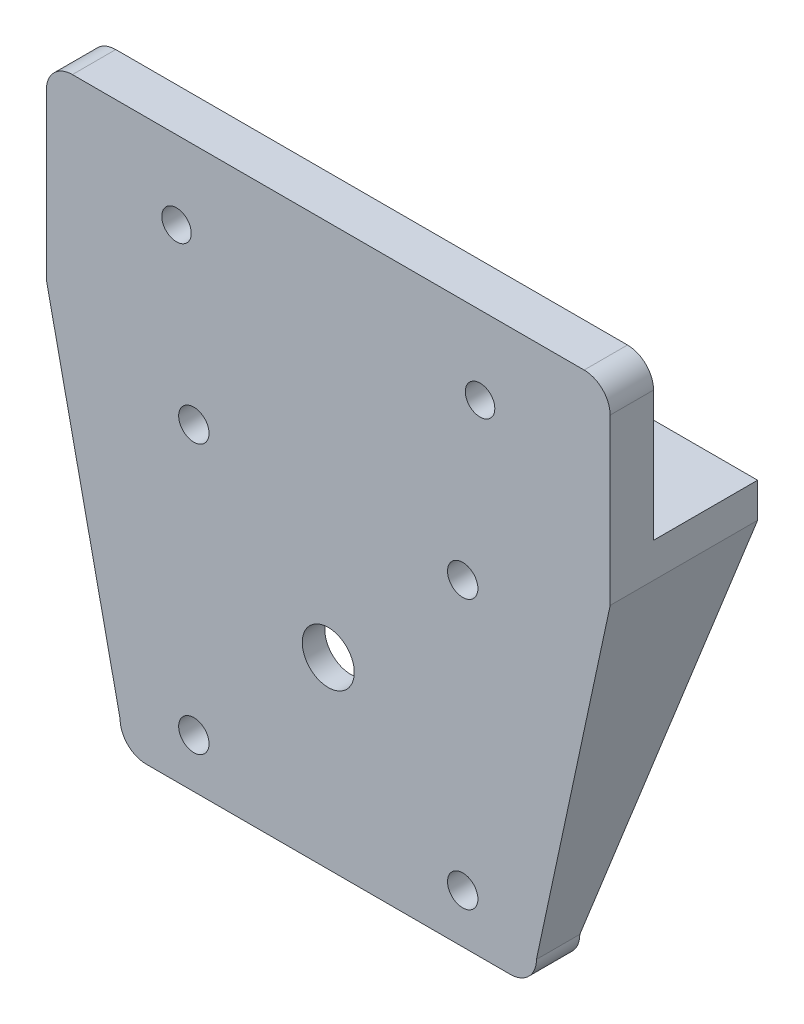
SolidWorks part; units mm, degrees
ref_plane "Ebene vorne" through (0, 0, 0) normal (0, 0, 1) x (1, 0, 0)
ref_plane "Ebene oben" through (0, 0, 0) normal (0, 1, 0) x (1, 0, 0)
ref_plane "Ebene rechts" through (0, 0, 0) normal (1, 0, 0) x (0, 0, -1)
sketch "Skizze1" plane through (0, 0, 0) normal (0, 0, 1) x (1, 0, 0)
  line L1 (-21, 32.3) -> (21, 32.3)
  line L2 (-24, 29.3) -> (-24, -29.3)
  line L3 (-21, -32.3) -> (21, -32.3)
  line L4 (24, 29.3) -> (24, -29.3)
  line L5 (-24, 32.3) -> (24, -32.3) construction
  line L6 (-24, -32.3) -> (24, 32.3) construction
  arc A0 (21, 32.3) -> (24, 29.3) centre (21, 29.3) cw
  arc A1 (-24, -29.3) -> (-21, -32.3) centre (-21, -29.3) ccw
  arc A2 (-21, 32.3) -> (-24, 29.3) centre (-21, 29.3) ccw
  arc A3 (21, -32.3) -> (24, -29.3) centre (21, -29.3) ccw
  point P0 (0, 0)
  dimension "D1" = 3
  dimension "D2" = 48
  dimension "D3" = 64.6
extrude "Aufsatz-Linear austragen1" add sketch "Skizze1" along normal blind 5
sketch "Skizze2" plane through (0, 0, 5) normal (0, 0, 1) x (1, 0, 0)
  line L0 (-15.5, 4.35) -> (15.5, -26.65) construction
  line L1 (-21, -32.3) -> (21, -32.3) construction
  line L2 (15.5, 4.35) -> (-15.5, -26.65) construction
  line L5 (21, 32.3) -> (-21, 32.3) construction
  line L6 (-17.5, 23.3) -> (17.5, 23.3) construction
  circle A0 centre (-15.5, -26.65) radius 1.75
  circle A1 centre (15.5, -26.65) radius 1.75
  circle A2 centre (15.5, 4.35) radius 1.75
  circle A3 centre (-15.5, 4.35) radius 1.75
  circle A4 centre (-17.5, 23.3) radius 1.7
  circle A5 centre (17.5, 23.3) radius 1.7
  point P12 (0, 32.3)
  point P13 (0, -11.15)
  point P15 (0, 23.3)
  point P23 (0, -32.3)
  dimension "D1" = 3.5
  dimension "D6" = 3.4
  dimension "D2" = 31
  dimension "D3" = 31
  dimension "D5" = 5.65
  dimension "D7" = 9
  dimension "D8" = 35
extrude "Schnitt-Linear austragen1" cut sketch "Skizze2" against normal through all
sketch "Skizze3" plane through (0, 0, 0) normal (0, 0, -1) x (-1, 0, 0)
  line L0 (15.5, -26.65) -> (-15.5, 4.35) construction
  line L1 (15.5, 4.35) -> (-15.5, -26.65) construction
  circle A0 centre (0, -11.15) radius 11.15
  dimension "D1" = 22.3
extrude "Schnitt-Linear austragen2" cut sketch "Skizze3" against normal blind 2.4
sketch "Skizze4" plane through (0, 0, 2.4) normal (0, 0, -1) x (-1, 0, 0)
  circle A0 centre (0, -11.15) radius 3
  dimension "D1" = 6
extrude "Schnitt-Linear austragen3" cut sketch "Skizze4" against normal through all
sketch "Skizze5" plane through (0, 0, 5) normal (0, 0, 1) x (1, 0, 0)
  line L0 (-24, 29.3) -> (-24, -29.3) construction
  line L1 (-17, 30.3) -> (-15.0597, 30.7851)
  line L2 (-17, 30.3) -> (-10, 2.3)
  line L3 (-10, 2.3) -> (-8.0597, 2.7851)
  line L4 (-15.0597, 30.7851) -> (-8.0597, 2.7851)
  line L5 (-17, 30.3) -> (-8.0597, 2.7851) construction
  line L6 (-10, 2.3) -> (-15.0597, 30.7851) construction
  line L7 (21, 32.3) -> (-21, 32.3) construction
  line L9 (-10, 30.3) -> (-8, 30.3)
  line L10 (-10, 30.3) -> (-10, 2.3)
  line L11 (-10, 2.3) -> (-8, 2.3)
  line L12 (-8, 30.3) -> (-8, 2.3)
  line L13 (-10, 30.3) -> (-8, 2.3) construction
  line L14 (-10, 2.3) -> (-8, 30.3) construction
  line L15 (-10, -12.7) -> (-8, -12.7)
  line L16 (-10, -12.7) -> (-10, 2.3)
  line L17 (-10, 2.3) -> (-8, 2.3)
  line L18 (-8, -12.7) -> (-8, 2.3)
  line L19 (-10, -12.7) -> (-8, 2.3) construction
  line L20 (-10, 2.3) -> (-8, -12.7) construction
  point P0 (-12.5299, 16.5425)
  point P9 (-9, 16.3)
  point P14 (-9, -5.2)
  dimension "D1" = 2
  dimension "D2" = 7
  dimension "D3" = 2
  dimension "D4" = 2
  dimension "D5" = 16
  dimension "D6" = 30
  dimension "D7" = 2
  dimension "D8" = 15
extrude "Aufsatz-Linear austragen2" [suppressed] add sketch "Skizze5" along normal blind 4 contours L10 L4 L1 L2 | L4 L10 L3 | L12 L9 L10 L4 L3 L11 | L16 L15 L18 L17
ref_plane "Ebene1" through (0, 0, 0) normal (-1, 0, 0) x (0, 0, 1)
mirror "Spiegeln1" [suppressed] about plane through (0, 0, 0) normal (-1, 0, 0)
sketch "Skizze6" [suppressed] plane through (0, 0, 3.2) normal (0, 0, 1) x (1, 0, 0)
  line L0 (0, 3.96) -> (0, -3.96) construction
  line L1 (-1, 30.3) -> (1, 30.3)
  line L2 (-1, 30.3) -> (-1, 2.6)
  line L3 (-1, 2.6) -> (1, 2.6)
  line L4 (1, 30.3) -> (1, 2.6)
  line L5 (-1, 30.3) -> (1, 2.6) construction
  line L6 (-1, 2.6) -> (1, 30.3) construction
  line L7 (-9.15, 30.3) -> (-7.15, 30.3) construction
  circle A0 centre (-15.5, 4.35) radius 1.75 construction
  point P0 (0, 16.45)
  dimension "D1" = 2
extrude "Aufsatz-Linear austragen3" [suppressed] add sketch "Skizze6" along normal blind 4
sketch "Skizze8" [suppressed] plane through (0, 0, 3.2) normal (0, 0, 1) x (1, 0, 0)
  line L5 (20.15, 32.3) -> (-20.15, 32.3) construction
  line L6 (-19.95, -29.3) -> (-23.15, -29.3)
  line L7 (-19.95, -29.3) -> (-19.95, 32.3)
  line L8 (-19.95, 32.3) -> (-20.15, 32.3)
  line L9 (-23.15, -29.3) -> (-23.15, 29.3)
  line L10 (-19.95, -29.3) -> (-23.15, 32.3) construction
  line L11 (-19.95, 32.3) -> (-23.15, -29.3) construction
  arc A0 (-20.15, 32.3) -> (-23.15, 29.3) centre (-20.15, 29.3) ccw
  point P0 (-21.55, 1.5)
  dimension "D2" = 3
  dimension "D1" = 3.2
extrude "Aufsatz-Linear austragen5" [suppressed] add sketch "Skizze8" along normal blind 4
mirror "Spiegeln2" [suppressed] about plane through (0, 0, 0) normal (-1, 0, 0)
sketch "Skizze9" plane through (0, 0, 0) normal (0, 0, -1) x (-1, 0, 0)
  line L0 (0, -2.75) -> (0, 2.75) construction
  line L1 (-32.5, 10.3) -> (32.5, 10.3)
  line L2 (-32.5, 10.3) -> (-32.5, 14.3)
  line L3 (-32.5, 14.3) -> (32.5, 14.3)
  line L4 (32.5, 10.3) -> (32.5, 14.3)
  line L5 (-32.5, 10.3) -> (32.5, 14.3) construction
  line L6 (-32.5, 14.3) -> (32.5, 10.3) construction
  line L8 (-21, 32.3) -> (21, 32.3) construction
  point P0 (0, 12.3)
  dimension "D1" = 18
  dimension "D2" = 4
  dimension "D3" = 65
extrude "Aufsatz-Linear austragen6" add sketch "Skizze9" along normal blind 12
fillet "Verrundung1" [suppressed] radius 2
sketch "Skizze13" plane through (0, 14.3, 0) normal (0, 1, 0) x (1, 0, 0)
  line L0 (21, -5) -> (-21, -5) construction
  line L1 (24, -5) -> (32.5, -5)
  line L2 (24, -5) -> (24, 0)
  line L3 (24, 0) -> (32.5, 0)
  line L4 (32.5, -5) -> (32.5, 0)
  line L5 (24, -5) -> (32.5, 0) construction
  line L6 (24, 0) -> (32.5, -5) construction
  line L7 (24, -5) -> (24, 0) construction
  point P0 (28.25, -2.5)
extrude "Aufsatz-Linear austragen8" add sketch "Skizze13" against normal up to surface (4 mm away) up to face at (0, 10.3, -4)
sketch "Skizze11" plane through (24, 0, 0) normal (1, 0, 0) x (0, 0, -1)
  line L0 (12, 10.3) -> (0, -29.3)
  line L2 (0, -29.3) -> (0, 10.3)
  line L3 (0, 10.3) -> (12, 10.3)
  line L4 (12, 14.3) -> (12, 10.3) construction
extrude "Aufsatz-Linear austragen7" add sketch "Skizze11" against normal blind 2.7
mirror "Spiegeln4" about plane through (0, 0, 0) normal (-1, 0, 0) of "Aufsatz-Linear austragen7", "Aufsatz-Linear austragen8"
sketch "Skizze14" plane through (0, 10.3, 0) normal (0, -1, 0) x (1, 0, 0)
  circle A0 centre (12.5, -6) radius 1.7
  circle A1 centre (-12.5, -6) radius 1.7
  dimension "D1" = 3.4
extrude "Schnitt-Linear austragen4" cut sketch "Skizze14" against normal through all
sketch "Skizze15" plane through (0, 10.3, 0) normal (0, -1, 0) x (-1, 0, 0)
  circle A0 centre (12.5, 6) radius 3.25
  circle A1 centre (-12.5, 6) radius 3.25
  dimension "D1" = 6.5
extrude "Schnitt-Linear austragen5" cut sketch "Skizze15" against normal blind 3.4
sketch "Skizze16" plane through (0, 0, 5) normal (0, 0, 1) x (1, 0, 0)
  line L0 (32.5, 10.3) -> (24, -29.3)
  line L1 (24, -29.3) -> (24, 10.3)
  line L2 (24, 10.3) -> (32.5, 10.3)
extrude "Aufsatz-Linear austragen9" add sketch "Skizze16" against normal up to surface (17 mm away)
sketch "Skizze17" plane through (0, 0, 5) normal (0, 0, 1) x (1, 0, 0)
  line L0 (21, 32.3) -> (32.5, 32.3)
  line L1 (32.5, 32.3) -> (32.5, 14.3)
  line L2 (32.5, 14.3) -> (24, 14.3)
  line L3 (24, 14.3) -> (21, 32.3)
  line L4 (24, 14.3) -> (24, 29.3) construction
extrude "Aufsatz-Linear austragen10" add sketch "Skizze17" against normal up to surface (5 mm away) up to face at (0, 25.5071, 0)
fillet "Verrundung4" radius 3 1 edges at (32.5, 32.3, 2.5)
mirror "Spiegeln5" about plane through (0, 0, 0) normal (-1, 0, 0) of "Verrundung4", "Aufsatz-Linear austragen10", "Aufsatz-Linear austragen9"
